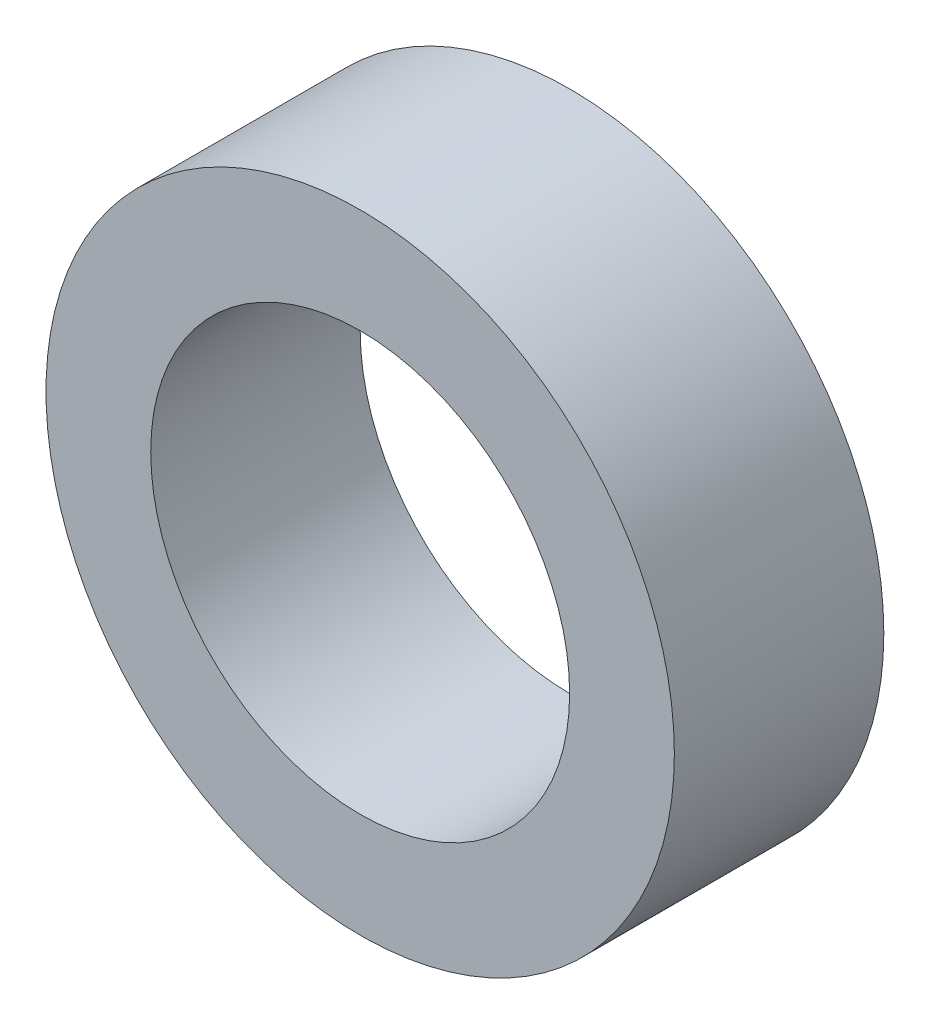
SolidWorks part; units mm, degrees
ref_plane "Front Plane" through (0, 0, 0) normal (0, 0, 1) x (1, 0, 0)
ref_plane "Top Plane" through (0, 0, 0) normal (0, 1, 0) x (1, 0, 0)
ref_plane "Right Plane" through (0, 0, 0) normal (1, 0, 0) x (0, 0, -1)
other "Configuration Table"
sketch "Sketch1" plane through (0, 0, 0) normal (0, 0, 1) x (1, 0, 0)
  circle A0 centre (0, 0) radius 1.905
  circle A1 centre (0, 0) radius 1.27
  dimension "D1" = 3.81
  dimension "D2" = 2.54
extrude "Boss-Extrude1" add sketch "Sketch1" along normal mid plane 1.27
scale "Scale1" scale about centroid uniform scaling yes scale factor 1.5
